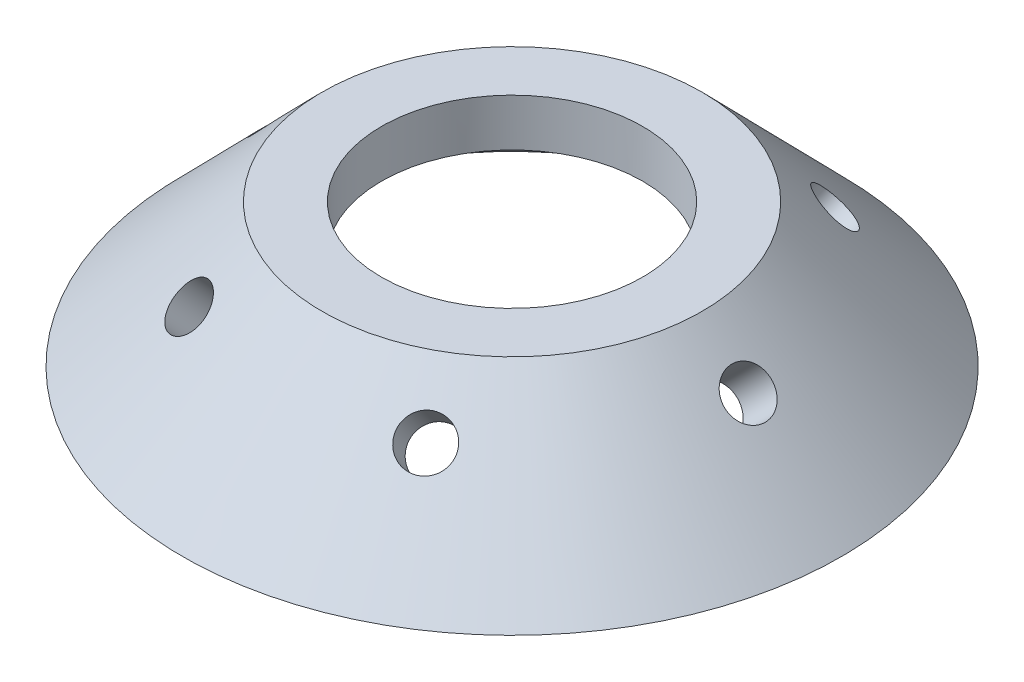
SolidWorks part; units mm, degrees
ref_plane "Front Plane" through (0, 0, 0) normal (0, 0, 1) x (1, 0, 0)
ref_plane "Top Plane" through (0, 0, 0) normal (0, 1, 0) x (1, 0, 0)
ref_plane "Right Plane" through (0, 0, 0) normal (1, 0, 0) x (0, 0, -1)
sketch "Sketch6" plane through (0, 0, 0) normal (0, 0, 1) x (1, 0, 0)
  line L2 (34.6969, -15) -> (20, 0)
  line L3 (20, 0) -> (0, 0)
  line L4 (34.6969, -15) -> (27.6969, -15)
  line L5 (27.6969, -15) -> (17.899, -5)
  line L6 (17.899, -5) -> (0, -5)
  line L7 (0, -5) -> (0, 0)
  line L8 (0, -5) -> (0, -15) construction
  line L9 (0, -15) -> (27.6969, -15) construction
  line L10 (34.6969, -15) -> (34.6969, -5) construction
  line L11 (34.6969, -5) -> (24.899, -5) construction
  dimension "D2" = 5
  dimension "D3" = 20
  dimension "D1" = 5
  dimension "D4" = 7
  dimension "D5" = 15
  dimension "D6" = 10
revolve "Revolve2" add sketch "Sketch6" angle 360 about L7
ref_plane "Plane1" through (10.2041, 9.9979, 0) normal (0.7143, 0.6999, 0) x (0, 0, -1)
sketch "Sketch11" plane through (0, 0, 0) normal (0, 1, 0) x (1, 0, 0)
  line L0 (-20, 0) -> (20, 0) construction
  circle A0 centre (0, 0) radius 13.75
  circle A2 centre (0, 0) radius 20 construction
  dimension "D1" = 27.5
extrude "Cut-Extrude1" cut sketch "Sketch11" against normal through all
sketch "Sketch24" plane through (10.2041, 9.9979, 0) normal (0.7143, 0.6999, 0) x (0, 0, -1)
  circle A0 centre (0, -20.9971) radius 2.5
  dimension "D1" = 5
extrude "Cut-Extrude2" cut sketch "Sketch24" against normal through all contours A0
pattern_circular "CirPattern10" count 6 over 360 about axis through (0, -5, 0) along (0, -1, 0) of "Cut-Extrude2"
equation "\"height\"= 3cm"
equation "\"D5@Sketch6\"=\"height\" * 0.5"
equation "\"D6@Sketch6\"=\"height\" * 0.5/2 + 0.25"
